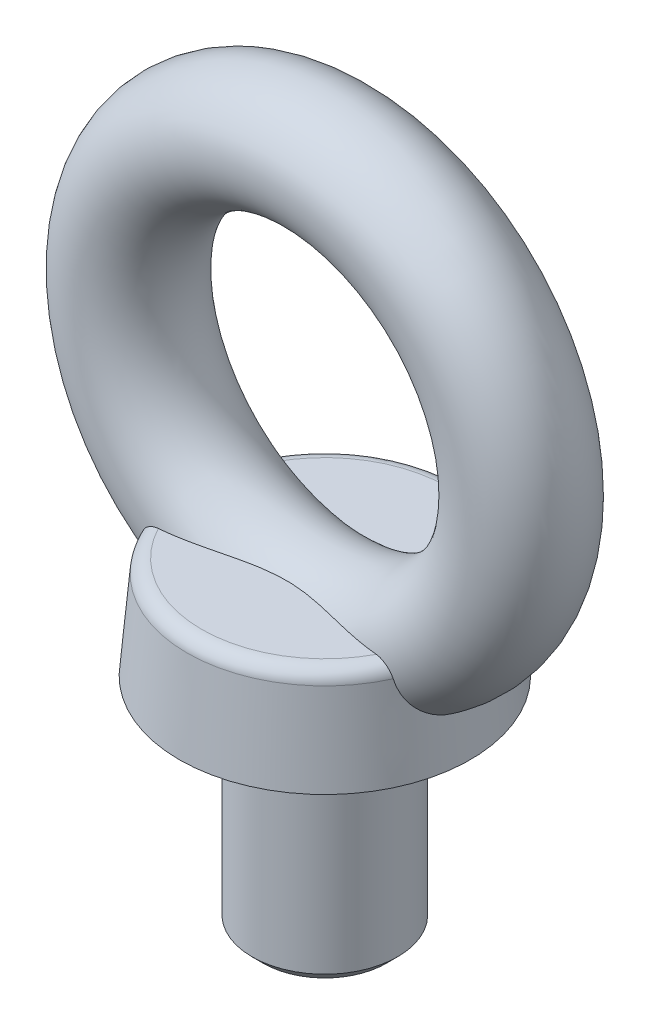
SolidWorks part; units mm, degrees
ref_plane "Płaszczyzna przednia" through (0, 0, 0) normal (0, 0, 1) x (1, 0, 0)
ref_plane "Płaszczyzna górna" through (0, 0, 0) normal (0, 1, 0) x (1, 0, 0)
ref_plane "Płaszczyzna prawa" through (0, 0, 0) normal (1, 0, 0) x (0, 0, -1)
sketch "Szkic1" plane through (0, 0, 0) normal (1, 0, 0) x (0, 0, -1)
  line L0 (8, 35) -> (-8, 35) construction
  circle A0 centre (0, 62) radius 8
sketch "Szkic2" plane through (0, 0, 0) normal (0, 0, 1) x (1, 0, 0)
  line L0 (0, 14) -> (16.9425, 14)
  line L1 (18.9349, 12.1743) -> (20, 0)
  line L2 (20, 0) -> (0, 0)
  line L3 (0, 0) -> (0, 14)
  line L4 (0, 0) -> (0, 14) construction
  arc A0 (16.9425, 14) -> (18.9349, 12.1743) centre (16.9425, 12) cw
revolve "Obrót1" add sketch "Szkic2" angle 360 about L4
revolve "Obrót2" add sketch "Szkic1" angle 360 about L0
sketch "Szkic3" plane through (0, 0, 0) normal (0, 0, 1) x (1, 0, 0)
  line L0 (0, 0) -> (10, 0)
  line L1 (10, 0) -> (10, -28.4665)
  line L2 (10, -28.4665) -> (8.4665, -30)
  line L3 (8.4665, -30) -> (0, -30)
  line L4 (0, -30) -> (0, 0)
  line L5 (0, -30) -> (0, 0) construction
revolve "Obrót3" add sketch "Szkic3" angle 360 about L5
cosmetic thread "Oznaczenie gwintu1" parameters "D1"=26, "D2"=16.933
sketch "Szkic4" plane through (0, 0, 0) normal (0, 0, 1) x (1, 0, 0)
  line L0 (9, 0) -> (9, -3)
  line L1 (9, -3) -> (10, -4)
  line L2 (10, -4) -> (10, 0)
  line L3 (10, 0) -> (9, 0)
  line L4 (0, -30) -> (0, 0) construction
revolve "Wycięcie-obrót1" cut sketch "Szkic4" angle 360 about L4
